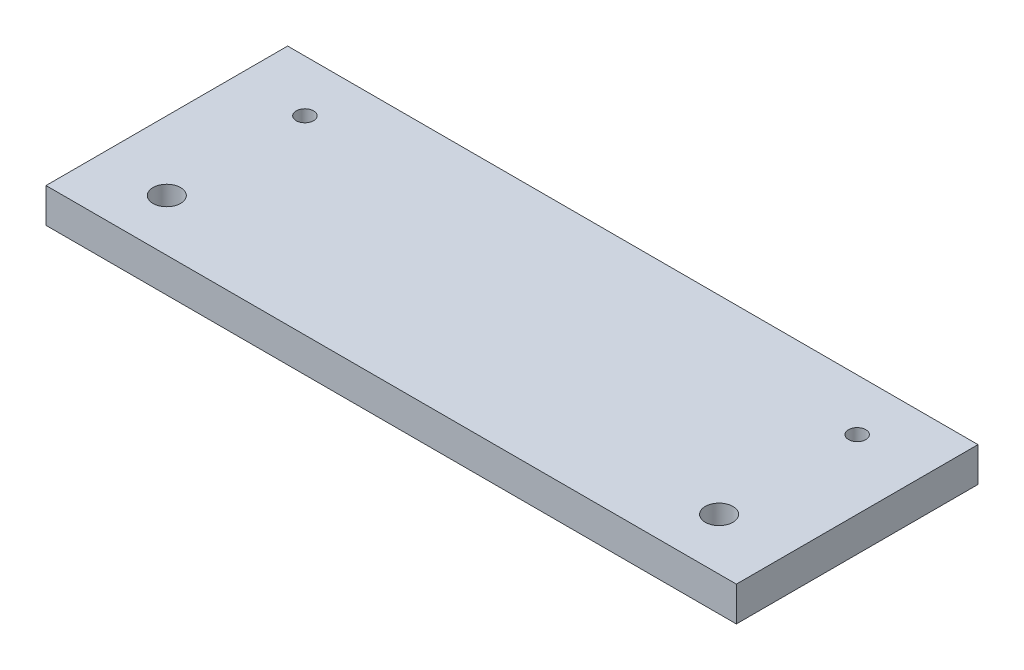
SolidWorks part; units mm, degrees
ref_plane "Front Plane" through (0, 0, 0) normal (0, 0, 1) x (1, 0, 0)
ref_plane "Top Plane" through (0, 0, 0) normal (0, 1, 0) x (1, 0, 0)
ref_plane "Right Plane" through (0, 0, 0) normal (1, 0, 0) x (0, 0, -1)
sketch "Sketch1" plane through (0, 0, 0) normal (0, 1, 0) x (1, 0, 0)
  line L1 (-100, -35) -> (100, -35)
  line L2 (-100, -35) -> (-100, 35)
  line L3 (-100, 35) -> (100, 35)
  line L4 (100, -35) -> (100, 35)
  line L5 (-100, -35) -> (100, 35) construction
  line L6 (-100, 35) -> (100, -35) construction
  point P0 (0, 0)
  dimension "D1" = 200
  dimension "D2" = 70
extrude "Boss-Extrude1" add sketch "Sketch1" along normal blind 10
sketch "Sketch2" plane through (0, 10, 0) normal (0, 1, 0) x (1, 0, 0)
  line L1 (0, 0) -> (0, 1.6072)
  line L4 (-100, -35) -> (100, -35) construction
  circle A0 centre (-80, -20) radius 4
  circle A2 centre (80, -20) radius 4
  dimension "D1" = 8
  dimension "D2" = 80
  dimension "D3" = 15
extrude "Cut-Extrude1" cut sketch "Sketch2" against normal blind 10 contours A0 | A2
sketch "Sketch4" plane through (0, 10, 0) normal (0, 1, 0) x (1, 0, 0)
  line L0 (100, 35) -> (-100, 35) construction
  line L2 (0, 0) -> (0, 10)
  circle A0 centre (-80, 20) radius 2.5
  circle A2 centre (80, 20) radius 2.5
  dimension "D1" = 5
  dimension "D2" = 15
extrude "Cut-Extrude2" cut sketch "Sketch4" against normal blind 10 contours A0 | A2
